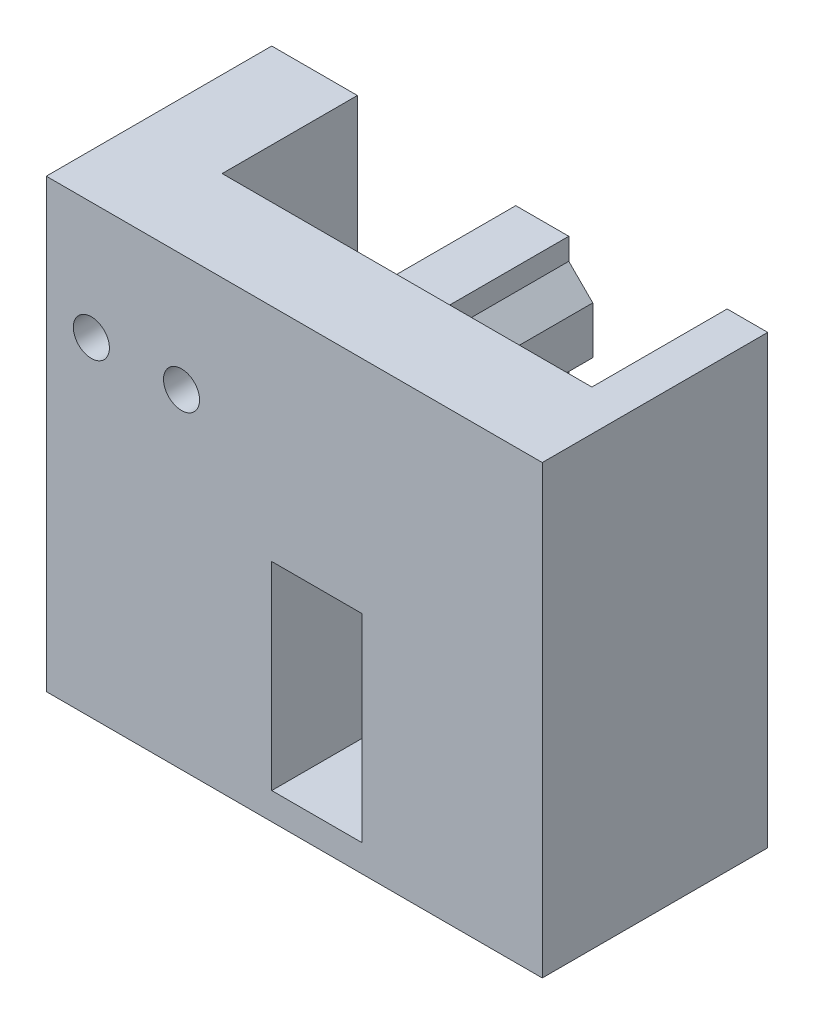
SolidWorks part; units mm, degrees
ref_plane "Front Plane" through (0, 0, 0) normal (0, 0, 1) x (1, 0, 0)
ref_plane "Top Plane" through (0, 0, 0) normal (0, 1, 0) x (1, 0, 0)
ref_plane "Right Plane" through (0, 0, 0) normal (1, 0, 0) x (0, 0, -1)
sketch "Sketch1" plane through (0, 0, 0) normal (0, 0, 1) x (1, 0, 0)
  line L0 (-16.2, -10) -> (-11.5, -10) construction
  line L1 (15, -20) -> (-40, -20)
  line L2 (15, -20) -> (15, 29.5)
  line L4 (-40, -20) -> (-40, 29.5)
  line L6 (10, 8.5) -> (10, 3.8) construction
  line L7 (-30, 28.5) -> (-30, 23.8) construction
  line L8 (-10, -10) -> (-10, 33.7547) construction
  line L9 (-8.5, -10) -> (-11.5, -10) construction
  line L10 (10.5, 10) -> (10.5, 29.5)
  line L11 (10.5, 10) -> (10.5, 3.4944)
  line L12 (10.5, 3.4944) -> (9.7, 2.6)
  line L13 (9.7, 2.6) -> (7.7, 2.6)
  line L14 (7.7, 2.6) -> (7.7, 5)
  line L17 (4.4, 2.6322) -> (4.4, -2.7831)
  line L20 (7.7, -5) -> (7.7, -2.6)
  line L21 (7.7, -2.6) -> (9.7, -2.6)
  line L22 (9.7, -2.6) -> (10.5, -3.4944)
  line L23 (10.5, -3.4944) -> (10.5, -10.5)
  line L24 (10.5, -10.5) -> (-30.5, -10.5)
  line L27 (8.5, -10) -> (3.8, -10) construction
  line L28 (8.2, -3.1) -> (9.3, -3.1) construction
  line L29 (8.2, 3.1) -> (9.3, 3.1) construction
  line L30 (3.9, 2.7565) -> (3.9, -2.7565) construction
  line L31 (8.2, 5.3) -> (8.2, 3.1) construction
  line L32 (8.2, -5.3) -> (8.2, -3.1) construction
  line L33 (10, -3.8) -> (10, -8.5) construction
  line L34 (7.7, -5) -> (6.7678, -5)
  line L35 (6.7678, -5) -> (4.4, -2.7831)
  line L37 (6.5607, -5.5) -> (8, -5.5) construction
  line L38 (4.4, 2.6322) -> (6.7678, 5)
  line L39 (3.9586, 2.8979) -> (6.5607, 5.5) construction
  line L40 (6.7678, 5) -> (7.7, 5)
  line L41 (6.5607, 5.5) -> (8, 5.5) construction
  line L43 (-26.7678, 5) -> (-27.7, 5)
  line L44 (-24.4, 2.6322) -> (-26.7678, 5)
  line L45 (-24.4, 2.6322) -> (-24.4, -2.7831)
  line L46 (-26.7678, -5) -> (-24.4, -2.7831)
  line L47 (-27.7, -5) -> (-26.7678, -5)
  line L48 (-27.7, -5) -> (-27.7, -2.6)
  line L49 (-27.7, -2.6) -> (-29.7, -2.6)
  line L50 (-29.7, -2.6) -> (-30.5, -3.4944)
  line L51 (-30.5, -3.4944) -> (-30.5, -10.5)
  line L52 (-30.5, 10) -> (-30.5, 3.4944)
  line L53 (-30.5, 3.4944) -> (-29.7, 2.6)
  line L54 (-29.7, 2.6) -> (-27.7, 2.6)
  line L55 (-27.7, 2.6) -> (-27.7, 5)
  line L56 (10.5, 29.5) -> (15, 29.5)
  line L58 (-40, 29.5) -> (-30.5, 29.5)
  line L59 (-30.5, 29.5) -> (-30.5, 10)
  dimension "D1" = 10
  dimension "D3" = 5
  dimension "D4" = 10
  dimension "D5" = 0.5
  dimension "D6" = 0.5
  dimension "D7" = 0.5
  dimension "D8" = 0.5
  dimension "D9" = 0.5
  dimension "D10" = 0.5
  dimension "D11" = 0.5
  dimension "D12" = 0.5
  dimension "D14" = 0.5
  dimension "D16" = 0.5
  dimension "D17" = 0.5
  dimension "D19" = 1.2
  dimension "D20" = 1.2
  dimension "D21" = 0.4
  dimension "D22" = 0.4
extrude "Boss-Extrude1" add sketch "Sketch1" against normal blind 15
sketch "Sketch3" plane through (0, 0, 0) normal (0, 0, 1) x (1, 0, 0)
  line L1 (15, -20) -> (-40, -20)
  line L2 (15, -20) -> (15, 29.5)
  line L3 (15, 29.5) -> (-40, 29.5)
  line L4 (-40, -20) -> (-40, 29.5)
extrude "Boss-Extrude2" add sketch "Sketch3" along normal blind 10
sketch "Sketch4" plane through (0, 0, 0) normal (0, 0, -1) x (-1, 0, 0)
  line L0 (12.9393, 25.2929) -> (15.6, 22.6322)
  line L1 (15.6, 22.6322) -> (15.6, 17.3678)
  line L2 (15.6, 17.3678) -> (12.9393, 14.7071)
  line L3 (12.9393, 14.7071) -> (12.9393, 12.3)
  line L4 (12.9393, 12.3) -> (7.0607, 12.3)
  line L5 (7.0607, 12.3) -> (7.0607, 14.7071)
  line L6 (7.0607, 14.7071) -> (4.4, 17.3678)
  line L7 (4.4, 17.3678) -> (4.4, 22.6322)
  line L8 (4.4, 22.6322) -> (7.0607, 25.2929)
  line L9 (7.0607, 25.2929) -> (7.0607, 27.7)
  line L10 (7.0607, 27.7) -> (12.9393, 27.7)
  line L11 (12.9393, 27.7) -> (12.9393, 25.2929)
  line L12 (6.5607, 11.8) -> (13.4393, 11.8) construction
  line L13 (6.5607, 28.2) -> (13.4393, 28.2) construction
  line L14 (3.9586, 22.8979) -> (6.5607, 25.5) construction
  line L15 (16.0414, 17.1021) -> (13.4393, 14.5) construction
  line L16 (13.4393, 14.5) -> (13.4393, 11.8) construction
  line L17 (6.5607, 14.5) -> (6.5607, 11.8) construction
  line L18 (3.9, 22.7565) -> (3.9, 17.2435) construction
  line L19 (16.1, 22.7565) -> (16.1, 17.2435) construction
  line L20 (16.0414, 22.8979) -> (13.4393, 25.5) construction
  line L21 (6.5607, 25.5) -> (6.5607, 28.2) construction
  line L22 (3.9586, 17.1021) -> (6.5607, 14.5) construction
  line L23 (13.4393, 25.5) -> (13.4393, 28.2) construction
  point P14 (10, 27.7)
  dimension "D1" = 0.5
  dimension "D2" = 0.5
  dimension "D3" = 0.5
  dimension "D4" = 0.5
  dimension "D5" = 0.5
  dimension "D6" = 0.5
  dimension "D7" = 0.5
  dimension "D8" = 0.5
  dimension "D9" = 0.5
  dimension "D10" = 0.5
  dimension "D11" = 0.5
  dimension "D13" = 0.5
extrude "Boss-Extrude3" add sketch "Sketch4" along normal blind 15 separate body
sketch "Sketch5" plane through (0, 0, 10) normal (0, 0, 1) x (1, 0, 0)
  line L0 (-40, 29.5) -> (-40, -20) construction
  line L1 (15, 29.5) -> (-40, 29.5) construction
  circle A0 centre (-35, 16.5) radius 2
  circle A1 centre (-25, 16.5) radius 2
  dimension "D1" = 4
  dimension "D2" = 4
  dimension "D3" = 5
  dimension "D4" = 13
  dimension "D5" = 15
  dimension "D6" = 13
extrude "Cut-Extrude1" cut sketch "Sketch5" against normal blind 7
sketch "Sketch6" plane through (0, -20, 0) normal (0, -1, 0) x (-1, 0, 0)
  line L1 (40, -10) -> (-15, -10) construction
  line L2 (40, 15) -> (40, -10) construction
  circle A0 centre (35, -1) radius 2
  dimension "D1" = 4
  dimension "D2" = 9
  dimension "D3" = 5
extrude "Cut-Extrude2" cut sketch "Sketch6" against normal blind 7
sketch "Sketch7" plane through (0, 0, 10) normal (0, 0, 1) x (1, 0, 0)
  line L0 (-40, -20) -> (15, -20) construction
  line L1 (-15, 5) -> (-5, 5)
  line L2 (-15, 5) -> (-15, -17)
  line L3 (-15, -17) -> (-5, -17)
  line L4 (-5, 5) -> (-5, -17)
  point P4 (-10, -17)
  point P7 (-12.5, -20)
  dimension "D1" = 2.5
  dimension "D2" = 3
  dimension "D3" = 22
  dimension "D4" = 10
extrude "Cut-Extrude3" cut sketch "Sketch7" against normal blind 43
